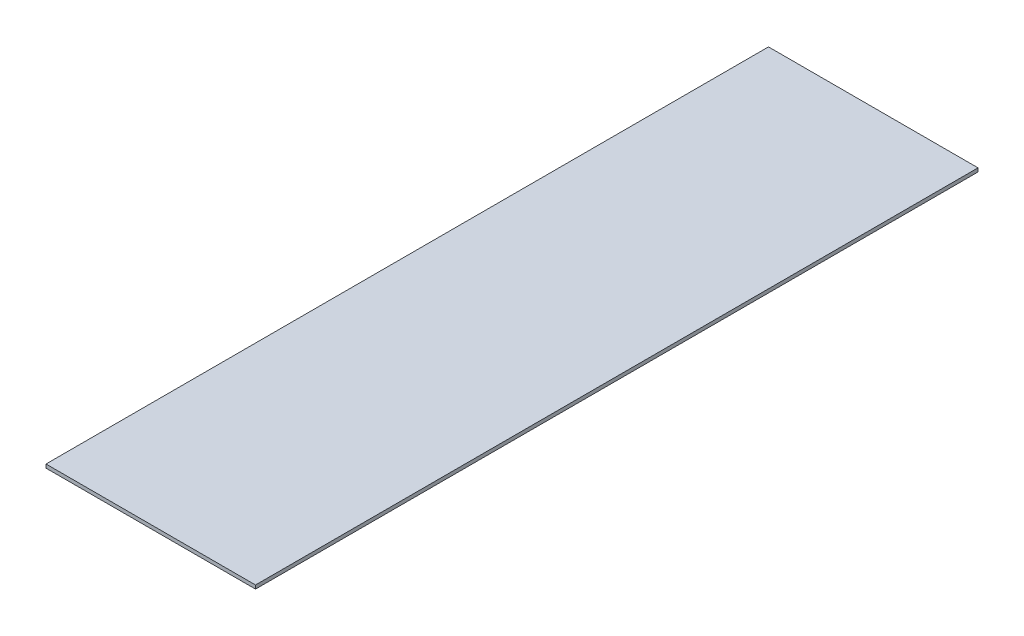
SolidWorks part; units mm, degrees
ref_plane "Front Plane" through (0, 0, 0) normal (0, 0, 1) x (1, 0, 0)
ref_plane "Top Plane" through (0, 0, 0) normal (0, 1, 0) x (1, 0, 0)
ref_plane "Right Plane" through (0, 0, 0) normal (1, 0, 0) x (0, 0, -1)
sketch "Sketch1" plane through (0, 0, 0) normal (0, 1, 0) x (1, 0, 0)
  line L1 (0, 0) -> (184.15, 0)
  line L2 (0, 0) -> (0, 685.8)
  line L3 (0, 685.8) -> (184.15, 685.8)
  line L4 (184.15, 0) -> (184.15, 685.8)
  dimension "D1" = 685.8
  dimension "D2" = 184.15
extrude "Boss-Extrude1" add sketch "Sketch1" along normal blind 3.175
sketch "Sketch2" plane through (0, 3.175, 0) normal (0, 1, 0) x (1, 0, 0)
  line L0 (184.15, 0) -> (184.15, 685.8) construction
  line L1 (0, 0) -> (184.15, 0)
  line L2 (0, 0) -> (0, 50.8)
  line L3 (0, 50.8) -> (184.15, 50.8)
  line L4 (184.15, 0) -> (184.15, 50.8)
  dimension "D1" = 50.8
extrude "Cut-Extrude1" cut sketch "Sketch2" against normal through all
